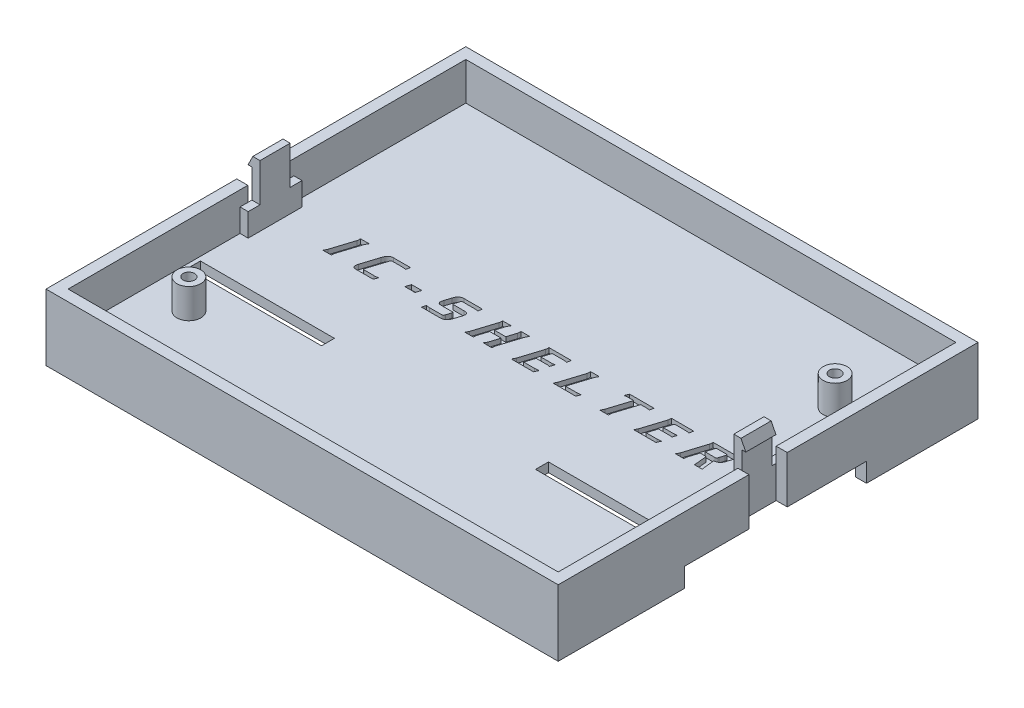
SolidWorks part; units mm, degrees
ref_plane "Alzado" through (0, 0, 0) normal (0, 0, 1) x (1, 0, 0)
ref_plane "Planta" through (0, 0, 0) normal (0, 1, 0) x (1, 0, 0)
ref_plane "Vista lateral" through (0, 0, 0) normal (1, 0, 0) x (0, 0, -1)
sketch "Sketch1" plane through (0, 0, 0) normal (0, 1, 0) x (1, 0, 0)
  line L1 (-53.5, -43.85) -> (53.5, -43.85)
  line L2 (-53.5, -43.85) -> (-53.5, 43.85)
  line L3 (-53.5, 43.85) -> (53.5, 43.85)
  line L4 (53.5, -43.85) -> (53.5, 43.85)
  line L5 (-53.5, -43.85) -> (53.5, 43.85) construction
  line L6 (-53.5, 43.85) -> (53.5, -43.85) construction
  point P0 (0, 0)
  dimension "D1" = 107
  dimension "D2" = 87.7
extrude "Boss-Extrude1" add sketch "Sketch1" along normal blind 13.85
sketch "Sketch2" plane through (0, 13.85, 0) normal (0, 1, 0) x (1, 0, 0)
  line L8 (51.19, -41.54) -> (51.19, 41.54)
  line L9 (51.19, 41.54) -> (-51.19, 41.54)
  line L10 (-51.19, 41.54) -> (-51.19, -41.54)
  line L11 (-51.19, -41.54) -> (51.19, -41.54)
  line L12 (51.19, -41.54) -> (51.19, 41.54)
  line L13 (51.19, 41.54) -> (-51.19, 41.54)
  line L14 (-51.19, 41.54) -> (-51.19, -41.54)
  line L15 (-51.19, -41.54) -> (51.19, -41.54)
  dimension "D1" = 2.31
extrude "Cut-Extrude1" cut sketch "Sketch2" against normal blind 7.9
sketch "Sketch3" plane through (0, 0, 0) normal (0, -1, 0) x (1, 0, 0)
  line L0 (-51.19, -41.54) -> (-51.19, 41.54) construction
  line L1 (-51.19, 41.54) -> (51.19, 41.54)
  line L2 (-51.19, 41.54) -> (-51.19, 19.24)
  line L3 (-51.19, 19.24) -> (-23.5, 19.24)
  line L4 (51.19, 41.54) -> (51.19, 19.24)
  line L5 (-51.19, 41.54) -> (51.19, 41.54) construction
  line L6 (51.19, 41.54) -> (51.19, -41.54) construction
  line L7 (-23.5, 19.24) -> (-23.5, 14.74)
  line L8 (-23.5, 14.74) -> (-49.4, 14.74)
  line L9 (-53.5, -43.85) -> (-53.5, 43.85) construction
  line L10 (-53.5, 17.44) -> (-53.5, -20.56)
  line L11 (-41.0677, -20.56) -> (-6.19, -20.56)
  line L12 (53.5, 43.85) -> (53.5, -43.85) construction
  line L13 (53.5, -20.56) -> (53.5, 17.44)
  line L14 (0, 0) -> (0, 18.4212) construction
  line L15 (23.5, 14.74) -> (23.5, 19.24)
  line L16 (23.5, 19.24) -> (51.19, 19.24)
  line L17 (-51.19, -41.54) -> (-10.19, -41.54)
  line L18 (51.19, -41.54) -> (51.19, -20.56)
  line L19 (-51.19, -41.54) -> (-51.19, -20.56)
  line L20 (-10.19, -41.54) -> (-10.19, -22.86)
  line L21 (10.19, -41.54) -> (10.19, -22.86)
  line L22 (6.19, -20.56) -> (6.19, -43.85)
  line L23 (-6.19, -43.85) -> (6.19, -43.85)
  line L24 (51.19, -20.56) -> (53.5, -20.56)
  line L25 (10.19, -41.54) -> (51.19, -41.54)
  line L26 (53.5, -43.85) -> (-53.5, -43.85) construction
  line L28 (51.19, -41.54) -> (-51.19, -41.54) construction
  line L29 (-10.19, -22.86) -> (-40.69, -22.86)
  line L30 (42.7044, -23.54) -> (40.69, -22.86)
  line L31 (-51.19, -20.56) -> (-53.5, -20.56)
  line L32 (-41.0677, -20.56) -> (-43.44, -21.3608)
  line L33 (-43.44, -21.3608) -> (-42.7044, -23.54)
  line L34 (-42.7044, -23.54) -> (-40.69, -22.86)
  line L35 (43.44, -21.3608) -> (42.7044, -23.54)
  line L36 (41.0677, -20.56) -> (43.44, -21.3608)
  line L37 (10.19, -22.86) -> (40.69, -22.86)
  line L38 (41.0677, -20.56) -> (6.19, -20.56)
  line L39 (-49.4, 17.44) -> (-53.5, 17.44)
  line L40 (-49.4, 17.44) -> (-49.4, 14.74)
  line L41 (49.4, 17.44) -> (53.5, 17.44)
  line L42 (49.4, 17.44) -> (49.4, 14.74)
  line L43 (23.5, 14.74) -> (49.4, 14.74)
  line L44 (-6.19, -20.56) -> (-6.19, -43.85)
  dimension "D1" = 22.3
  dimension "D2" = 30
  dimension "D3" = 4.5
  dimension "D4" = 4
  dimension "D5" = 4
  dimension "D6" = 41
  dimension "D7" = 2.3
  dimension "D8" = 7.75
  dimension "D9" = 2.3
  dimension "D10" = 35.3
  dimension "D11" = 18
  dimension "D12" = 30.5
  dimension "D13" = 30.5
  dimension "D14" = 25.9
  dimension "D15" = 1.8
extrude "Cut-Extrude2" cut sketch "Sketch3" against normal blind 4
sketch "Sketch4" plane through (0, 5.95, 0) normal (0, 1, 0) x (1, 0, 0)
  circle A0 centre (42.5, 25) radius 1.2
  circle A1 centre (-42.5, -25) radius 1.2
  circle A2 centre (-42.5, -25) radius 2.5
  circle A3 centre (42.5, 25) radius 2.5
  dimension "D1" = 2.4
  dimension "D6" = 5
  dimension "D2" = 25
  dimension "D3" = 25
  dimension "D4" = 42.5
  dimension "D5" = 42.5
extrude "Boss-Extrude2" add sketch "Sketch4" along normal blind 6.2
sketch "Sketch5" plane through (0, 5.95, 0) normal (0, 1, 0) x (1, 0, 0)
  line L0 (-49.4, -17.44) -> (-53.5, -17.44) construction
  line L1 (-50.36, -17.44) -> (-22.36, -17.44)
  line L2 (-50.36, -17.44) -> (-50.36, -14.74)
  line L3 (-50.36, -14.74) -> (-22.36, -14.74)
  line L4 (-22.36, -17.44) -> (-22.36, -14.74)
  line L5 (-23.5, -14.74) -> (-49.4, -14.74) construction
  line L6 (-53.5, 43.85) -> (-53.5, -43.85) construction
  line L7 (0, 0) -> (0, -23.0009) construction
  line L8 (22.36, -17.44) -> (22.36, -14.74)
  line L9 (50.36, -14.74) -> (22.36, -14.74)
  line L10 (50.36, -17.44) -> (50.36, -14.74)
  line L11 (50.36, -17.44) -> (22.36, -17.44)
  dimension "D1" = 3.14
  dimension "D2" = 28
extrude "Cut-Extrude3" cut sketch "Sketch5" against normal blind 3.5
chamfer "Chamfer1" distance 2 angle 45 2 edges at (-36.45, 2.45, 14.74) (36.45, 2.45, 14.74)
sketch "Sketch6" plane through (-53.5, 0, 0) normal (-1, 0, 0) x (0, 0, 1)
  line L0 (-43.85, 13.85) -> (43.85, 13.85) construction
  line L1 (-4, 13.85) -> (4, 13.85)
  line L2 (-4, 13.85) -> (-4, 4)
  line L3 (-4, 4) -> (4, 4)
  line L4 (4, 13.85) -> (4, 4)
  line L5 (17.44, 4) -> (-20.56, 4) construction
  point P8 (0, 4)
  dimension "D1" = 8
extrude "Cut-Extrude4" cut sketch "Sketch6" against normal blind 2.31
sketch "Sketch7" plane through (-51.19, 0, 0) normal (1, 0, 0) x (0, 0, -1)
  line L0 (-4, 5.95) -> (-41.54, 5.95) construction
  line L1 (-5.625, 5.95) -> (5.625, 5.95)
  line L2 (-5.625, 5.95) -> (-5.625, 10.75)
  line L3 (-5.625, 10.75) -> (5.625, 10.75)
  line L4 (5.625, 5.95) -> (5.625, 10.75)
  point P6 (0, 5.95)
  dimension "D1" = 11.25
  dimension "D2" = 4.8
extrude "Boss-Extrude3" add sketch "Sketch7" along normal blind 1.7
sketch "Sketch8" plane through (0, 0, 0) normal (0, 0, 1) x (1, 0, 0)
  line L0 (-49.49, 10.75) -> (-49.49, 18.75)
  line L1 (-49.49, 18.75) -> (-50.99, 18.75)
  line L2 (-50.99, 18.75) -> (-51.99, 16.75)
  line L3 (-51.99, 16.75) -> (-51.19, 16.75)
  line L4 (-51.19, 16.75) -> (-51.19, 10.75)
  line L5 (-51.19, 10.75) -> (-49.49, 10.75)
  line L6 (51.19, 5.95) -> (-51.19, 5.95) construction
  dimension "D1" = 12.8
  dimension "D2" = 2.5
  dimension "D3" = 2
  dimension "D4" = 1.5
extrude "Boss-Extrude4" add sketch "Sketch8" along normal mid plane 6.3
mirror "Mirror1" about plane through (0, 0, 0) normal (1, 0, 0) of "Boss-Extrude4", "Boss-Extrude3", "Cut-Extrude4"
sketch "Sketch10" plane through (0, 5.95, 0) normal (0, 1, 0) x (1, 0, 0)
  line L0 (-49.49, 0) -> (49.49, 0) construction
  line L1 (-49.49, -5.625) -> (-49.49, 5.625) construction
  line L2 (49.49, -5.625) -> (49.49, 5.625) construction
  text T0 "IC-SHELTER" font "Dungeon" height 6
extrude "Cut-Extrude5" cut sketch "Sketch10" against normal blind 1
